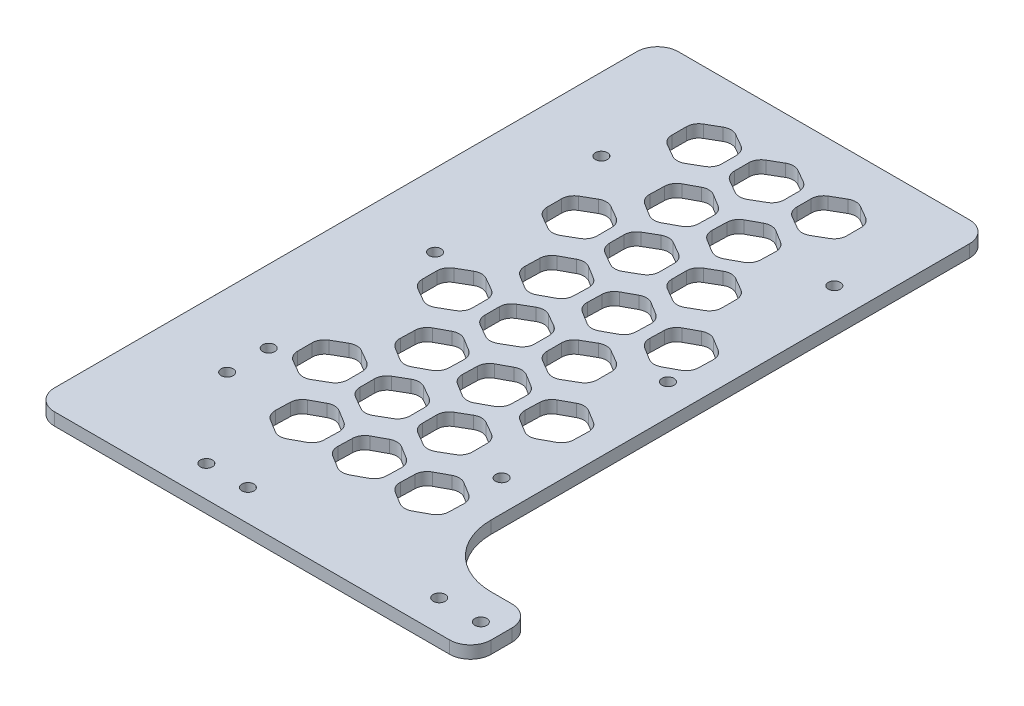
SolidWorks part; units mm, degrees
material "Thornel Mat VMA"
ref_plane "前视基准面" through (0, 0, 0) normal (0, 0, 1) x (1, 0, 0)
ref_plane "上视基准面" through (0, 0, 0) normal (0, 1, 0) x (1, 0, 0)
ref_plane "右视基准面" through (0, 0, 0) normal (1, 0, 0) x (0, 0, -1)
other "Configuration Table"
sketch "草图1" plane through (0, 0, 0) normal (0, 1, 0) x (1, 0, 0)
  line L0 (40, 75) -> (40, -60)
  line L1 (-40, -75) -> (40, -75)
  line L2 (-40, -75) -> (-40, 75)
  line L3 (-40, 75) -> (40, 75)
  line L4 (40, -75) -> (40, 75) construction
  line L5 (-40, -75) -> (40, 75) construction
  line L6 (-40, 75) -> (40, -75) construction
  line L7 (40, -60) -> (65, -60)
  line L8 (65, -60) -> (65, -75)
  line L9 (65, -75) -> (40, -75)
  line L10 (-50.4431, -67.5) -> (109.1266, -67.5) construction
  circle A0 centre (50, -67.5) radius 1.45
  circle A1 centre (60, -67.5) radius 1.45
  point P0 (0, 0)
  dimension "D7" = 10
  dimension "D8" = 2.9
  dimension "D1" = 80
  dimension "D2" = 150
  dimension "D3" = 15
  dimension "D4" = 25
  dimension "D5" = 7.5
  dimension "D6" = 10
extrude "凸台-拉伸1" add sketch "草图1" along normal blind 3
fillet "圆角1" radius 5 5 edges at (40, 1.5, -75) (65, 1.5, 75) (-40, 1.5, 75) (-40, 1.5, -75) (65, 1.5, 60)
fillet "圆角2" radius 15 1 edges at (40, 1.5, 60)
sketch "草图2" plane through (0, 3, 0) normal (0, 1, 0) x (1, 0, 0)
  circle A0 centre (4, -67.5) radius 1.45 construction
  circle A1 centre (-6, -67.5) radius 1.45 construction
  circle A2 centre (-22.5, -46) radius 1.45 construction
  circle A3 centre (-22.5, -36) radius 1.45 construction
  circle A4 centre (4, -67.5) radius 1.45
  circle A5 centre (-6, -67.5) radius 1.45
  circle A6 centre (-22.5, -46) radius 1.45
  circle A7 centre (-22.5, -36) radius 1.45
extrude "切除-拉伸1" cut sketch "草图2" against normal through all
sketch "草图3" plane through (0, 3, 0) normal (0, 1, 0) x (1, 0, 0)
  line L0 (-22.5, -46) -> (-22.5, 81.0235) construction
  line L1 (32.5, 83.4378) -> (32.5, -84.3822) construction
  line L2 (40, -45) -> (40, 70) construction
  line L3 (-35, -75) -> (60, -75) construction
  circle A0 centre (32.5, -35) radius 1.45
  circle A1 centre (32.5, 5) radius 1.45
  circle A2 centre (32.5, 45) radius 1.45
  circle A3 centre (-22.5, 44) radius 1.45
  circle A4 centre (-22.5, 4) radius 1.45
  circle A5 centre (-22.5, -36) radius 1.45 construction
  dimension "D2" = 2.9
  dimension "D3" = 40
  dimension "D4" = 40
  dimension "D5" = 40
  dimension "D6" = 40
  dimension "D7" = 40
  dimension "D1" = 7.5
extrude "切除-拉伸2" cut sketch "草图3" against normal through all
sketch "草图4" plane through (0, 3, 0) normal (0, 1, 0) x (1, 0, 0)
  line L0 (8.5893, 62.0825) -> (2.5893, 65.5466)
  line L1 (-6.4107, 62.0825) -> (-12.4107, 65.5466)
  line L2 (-12.4107, 65.5466) -> (-18.4107, 62.0825)
  line L3 (-18.4107, 62.0825) -> (-18.4107, 55.1543)
  line L4 (-18.4107, 55.1543) -> (-12.4107, 51.6902)
  line L5 (-12.4107, 51.6902) -> (-6.4107, 55.1543)
  line L6 (-6.4107, 55.1543) -> (-6.4107, 62.0825)
  line L7 (3.3955, 46.736) -> (-2.5041, 50.3685)
  line L8 (-2.5041, 50.3685) -> (-8.5997, 47.0755)
  line L9 (-8.5997, 47.0755) -> (-8.7957, 40.15)
  line L10 (-8.7957, 40.15) -> (-2.8961, 36.5176)
  line L11 (-2.8961, 36.5176) -> (3.1995, 39.8106)
  line L12 (3.1995, 39.8106) -> (3.3955, 46.736)
  line L13 (2.5893, 65.5466) -> (-3.4107, 62.0825)
  line L14 (-3.4107, 62.0825) -> (-3.4107, 55.1543)
  line L15 (-3.4107, 55.1543) -> (2.5893, 51.6902)
  line L16 (2.5893, 51.6902) -> (8.5893, 55.1543)
  line L17 (8.5893, 55.1543) -> (8.5893, 62.0825)
  line L18 (18.3955, 46.736) -> (12.4959, 50.3685)
  line L19 (12.4959, 50.3685) -> (6.4003, 47.0755)
  line L20 (6.4003, 47.0755) -> (6.2043, 40.15)
  line L21 (6.2043, 40.15) -> (12.1039, 36.5176)
  line L22 (12.1039, 36.5176) -> (18.1995, 39.8106)
  line L23 (18.1995, 39.8106) -> (18.3955, 46.736)
  line L24 (23.5893, 62.0825) -> (17.5893, 65.5466)
  line L25 (17.5893, 65.5466) -> (11.5893, 62.0825)
  line L26 (11.5893, 62.0825) -> (11.5893, 55.1543)
  line L27 (11.5893, 55.1543) -> (17.5893, 51.6902)
  line L28 (17.5893, 51.6902) -> (23.5893, 55.1543)
  line L29 (23.5893, 55.1543) -> (23.5893, 62.0825)
  line L36 (8.5893, 32.0825) -> (2.5893, 35.5466)
  line L37 (2.5893, 35.5466) -> (-3.4107, 32.0825)
  line L38 (-3.4107, 32.0825) -> (-3.4107, 25.1543)
  line L39 (-3.4107, 25.1543) -> (2.5893, 21.6902)
  line L40 (2.5893, 21.6902) -> (8.5893, 25.1543)
  line L41 (8.5893, 25.1543) -> (8.5893, 32.0825)
  line L42 (18.3955, 16.736) -> (12.4959, 20.3685)
  line L43 (12.4959, 20.3685) -> (6.4003, 17.0755)
  line L44 (6.4003, 17.0755) -> (6.2043, 10.15)
  line L45 (6.2043, 10.15) -> (12.1039, 6.5176)
  line L46 (12.1039, 6.5176) -> (18.1995, 9.8106)
  line L47 (18.1995, 9.8106) -> (18.3955, 16.736)
  line L48 (23.5893, 32.0825) -> (17.5893, 35.5466)
  line L49 (17.5893, 35.5466) -> (11.5893, 32.0825)
  line L50 (11.5893, 32.0825) -> (11.5893, 25.1543)
  line L51 (11.5893, 25.1543) -> (17.5893, 21.6902)
  line L52 (17.5893, 21.6902) -> (23.5893, 25.1543)
  line L53 (23.5893, 25.1543) -> (23.5893, 32.0825)
  line L54 (33.3955, 16.736) -> (27.4959, 20.3685)
  line L55 (27.4959, 20.3685) -> (21.4003, 17.0755)
  line L56 (21.4003, 17.0755) -> (21.2043, 10.15)
  line L57 (21.2043, 10.15) -> (27.1039, 6.5176)
  line L58 (27.1039, 6.5176) -> (33.1995, 9.8106)
  line L59 (33.1995, 9.8106) -> (33.3955, 16.736)
  line L60 (8.5893, 2.0825) -> (2.5893, 5.5466)
  line L61 (2.5893, 5.5466) -> (-3.4107, 2.0825)
  line L62 (-3.4107, 2.0825) -> (-3.4107, -4.8457)
  line L63 (-3.4107, -4.8457) -> (2.5893, -8.3098)
  line L64 (2.5893, -8.3098) -> (8.5893, -4.8457)
  line L65 (8.5893, -4.8457) -> (8.5893, 2.0825)
  line L66 (18.3955, -13.264) -> (12.4959, -9.6315)
  line L67 (12.4959, -9.6315) -> (6.4003, -12.9245)
  line L68 (6.4003, -12.9245) -> (6.2043, -19.85)
  line L69 (6.2043, -19.85) -> (12.1039, -23.4824)
  line L70 (12.1039, -23.4824) -> (18.1995, -20.1894)
  line L71 (18.1995, -20.1894) -> (18.3955, -13.264)
  line L72 (23.5893, 2.0825) -> (17.5893, 5.5466)
  line L73 (17.5893, 5.5466) -> (11.5893, 2.0825)
  line L74 (11.5893, 2.0825) -> (11.5893, -4.8457)
  line L75 (11.5893, -4.8457) -> (17.5893, -8.3098)
  line L76 (17.5893, -8.3098) -> (23.5893, -4.8457)
  line L77 (23.5893, -4.8457) -> (23.5893, 2.0825)
  line L78 (33.3955, -13.264) -> (27.4959, -9.6315)
  line L79 (27.4959, -9.6315) -> (21.4003, -12.9245)
  line L80 (21.4003, -12.9245) -> (21.2043, -19.85)
  line L81 (21.2043, -19.85) -> (27.1039, -23.4824)
  line L82 (27.1039, -23.4824) -> (33.1995, -20.1894)
  line L83 (33.1995, -20.1894) -> (33.3955, -13.264)
  line L84 (8.5893, -27.9175) -> (2.5893, -24.4534)
  line L85 (2.5893, -24.4534) -> (-3.4107, -27.9175)
  line L86 (-3.4107, -27.9175) -> (-3.4107, -34.8457)
  line L87 (-3.4107, -34.8457) -> (2.5893, -38.3098)
  line L88 (2.5893, -38.3098) -> (8.5893, -34.8457)
  line L89 (8.5893, -34.8457) -> (8.5893, -27.9175)
  line L90 (18.3955, -43.264) -> (12.4959, -39.6315)
  line L91 (12.4959, -39.6315) -> (6.4003, -42.9245)
  line L92 (6.4003, -42.9245) -> (6.2043, -49.85)
  line L93 (6.2043, -49.85) -> (12.1039, -53.4824)
  line L94 (12.1039, -53.4824) -> (18.1995, -50.1894)
  line L95 (18.1995, -50.1894) -> (18.3955, -43.264)
  line L96 (23.5893, -27.9175) -> (17.5893, -24.4534)
  line L97 (17.5893, -24.4534) -> (11.5893, -27.9175)
  line L98 (11.5893, -27.9175) -> (11.5893, -34.8457)
  line L99 (11.5893, -34.8457) -> (17.5893, -38.3098)
  line L100 (17.5893, -38.3098) -> (23.5893, -34.8457)
  line L101 (23.5893, -34.8457) -> (23.5893, -27.9175)
  line L102 (33.3955, -43.264) -> (27.4959, -39.6315)
  line L103 (27.4959, -39.6315) -> (21.4003, -42.9245)
  line L104 (21.4003, -42.9245) -> (21.2043, -49.85)
  line L105 (21.2043, -49.85) -> (27.1039, -53.4824)
  line L106 (27.1039, -53.4824) -> (33.1995, -50.1894)
  line L107 (33.1995, -50.1894) -> (33.3955, -43.264)
  line L108 (-6.4107, 32.0825) -> (-12.4107, 35.5466)
  line L109 (-12.4107, 35.5466) -> (-18.4107, 32.0825)
  line L110 (-18.4107, 32.0825) -> (-18.4107, 25.1543)
  line L111 (-18.4107, 25.1543) -> (-12.4107, 21.6902)
  line L112 (-12.4107, 21.6902) -> (-6.4107, 25.1543)
  line L113 (-6.4107, 25.1543) -> (-6.4107, 32.0825)
  line L114 (3.3955, 16.736) -> (-2.5041, 20.3685)
  line L115 (-2.5041, 20.3685) -> (-8.5997, 17.0755)
  line L116 (-8.5997, 17.0755) -> (-8.7957, 10.15)
  line L117 (-8.7957, 10.15) -> (-2.8961, 6.5176)
  line L118 (-2.8961, 6.5176) -> (3.1995, 9.8106)
  line L119 (3.1995, 9.8106) -> (3.3955, 16.736)
  line L120 (-6.4107, 2.0825) -> (-12.4107, 5.5466)
  line L121 (-12.4107, 5.5466) -> (-18.4107, 2.0825)
  line L122 (-18.4107, 2.0825) -> (-18.4107, -4.8457)
  line L123 (-18.4107, -4.8457) -> (-12.4107, -8.3098)
  line L124 (-12.4107, -8.3098) -> (-6.4107, -4.8457)
  line L125 (-6.4107, -4.8457) -> (-6.4107, 2.0825)
  line L126 (3.3955, -13.264) -> (-2.5041, -9.6315)
  line L127 (-2.5041, -9.6315) -> (-8.5997, -12.9245)
  line L128 (-8.5997, -12.9245) -> (-8.7957, -19.85)
  line L129 (-8.7957, -19.85) -> (-2.8961, -23.4824)
  line L130 (-2.8961, -23.4824) -> (3.1995, -20.1894)
  line L131 (3.1995, -20.1894) -> (3.3955, -13.264)
  line L132 (-6.4107, -27.9175) -> (-12.4107, -24.4534)
  line L133 (-12.4107, -24.4534) -> (-18.4107, -27.9175)
  line L134 (-18.4107, -27.9175) -> (-18.4107, -34.8457)
  line L135 (-18.4107, -34.8457) -> (-12.4107, -38.3098)
  line L136 (-12.4107, -38.3098) -> (-6.4107, -34.8457)
  line L137 (-6.4107, -34.8457) -> (-6.4107, -27.9175)
  line L138 (3.3955, -43.264) -> (-2.5041, -39.6315)
  line L139 (-2.5041, -39.6315) -> (-8.5997, -42.9245)
  line L140 (-8.5997, -42.9245) -> (-8.7957, -49.85)
  line L141 (-8.7957, -49.85) -> (-2.8961, -53.4824)
  line L142 (-2.8961, -53.4824) -> (3.1995, -50.1894)
  line L143 (3.1995, -50.1894) -> (3.3955, -43.264)
  line L144 (27.4959, 50.3685) -> (21.4003, 47.0755) [skipped]
  line L145 (21.4003, 47.0755) -> (21.2043, 40.15) [skipped]
  line L146 (21.2043, 40.15) -> (27.1039, 36.5176) [skipped]
  line L147 (33.1995, 39.8106) -> (33.3955, 46.736) [skipped]
  line L148 (33.3955, 46.736) -> (27.4959, 50.3685) [skipped]
  line L149 (27.1039, 36.5176) -> (33.1995, 39.8106) [skipped]
  circle A0 centre (-12.4107, 58.6184) radius 6 construction
  circle A1 centre (-2.7001, 43.443) radius 6 construction
  point P1 (-5.5519, 48.722)
  dimension "D1" = 12
  dimension "D2" = 12
  dimension "D3" = 6
  dimension "D4" = 3
  dimension "D5" = 4
extrude "切除-拉伸3" cut sketch "草图4" against normal through all
fillet "圆角3" radius 3 131 edges at (-6.4107, 1.5, -55.1543) (-12.4107, 1.5, -51.6902) (-18.4107, 1.5, -55.1543) (-6.4107, 1.5, -62.0825) (3.1995, 1.5, 50.1894) (-2.8961, 1.5, 53.4824) (-8.7957, 1.5, 49.85) (-8.5997, 1.5, 42.9245) (-2.5041, 1.5, 39.6315) (3.3955, 1.5, 43.264) (-6.4107, 1.5, 34.8457) (-12.4107, 1.5, 38.3098) (-18.4107, 1.5, 34.8457) (-18.4107, 1.5, 27.9175) (-12.4107, 1.5, 24.4534) (-6.4107, 1.5, 27.9175) (3.1995, 1.5, 20.1894) (-2.8961, 1.5, 23.4824) (-8.7957, 1.5, 19.85) (-8.5997, 1.5, 12.9245) (-2.5041, 1.5, 9.6315) (3.3955, 1.5, 13.264) (-6.4107, 1.5, 4.8457) (-12.4107, 1.5, 8.3098) (-18.4107, 1.5, 4.8457) (-18.4107, 1.5, -2.0825) (-12.4107, 1.5, -5.5466) (-6.4107, 1.5, -2.0825) (3.1995, 1.5, -9.8106) (-2.8961, 1.5, -6.5176) (-8.7957, 1.5, -10.15) (-8.5997, 1.5, -17.0755) (-2.5041, 1.5, -20.3685) (3.3955, 1.5, -16.736) (-6.4107, 1.5, -25.1543) (-12.4107, 1.5, -21.6902) (-18.4107, 1.5, -25.1543) (-18.4107, 1.5, -32.0825) (-12.4107, 1.5, -35.5466) (8.5893, 1.5, 34.8457) (2.5893, 1.5, 38.3098) (-3.4107, 1.5, 34.8457) (2.5893, 1.5, 24.4534) (8.5893, 1.5, 27.9175) (18.1995, 1.5, 50.1894) (12.1039, 1.5, 53.4824) (6.2043, 1.5, 49.85) (6.4003, 1.5, 42.9245) (18.3955, 1.5, 43.264) (23.5893, 1.5, 34.8457) (17.5893, 1.5, 38.3098) (11.5893, 1.5, 34.8457) (11.5893, 1.5, 27.9175) (17.5893, 1.5, 24.4534) (23.5893, 1.5, 27.9175) (33.1995, 1.5, 50.1894) (27.1039, 1.5, 53.4824) (21.2043, 1.5, 49.85) (21.4003, 1.5, 42.9245) (27.4959, 1.5, 39.6315) (8.5893, 1.5, 4.8457) (2.5893, 1.5, 8.3098) (-3.4107, 1.5, 4.8457) (-3.4107, 1.5, -2.0825) (2.5893, 1.5, -5.5466) (8.5893, 1.5, -2.0825) (18.1995, 1.5, 20.1894) (12.1039, 1.5, 23.4824) (6.2043, 1.5, 19.85) (12.4959, 1.5, 9.6315) (18.3955, 1.5, 13.264) (23.5893, 1.5, 4.8457) (17.5893, 1.5, 8.3098) (11.5893, 1.5, 4.8457) (11.5893, 1.5, -2.0825) (23.5893, 1.5, -2.0825) (33.1995, 1.5, 20.1894) (27.1039, 1.5, 23.4824) (21.2043, 1.5, 19.85) (21.4003, 1.5, 12.9245) (27.4959, 1.5, 9.6315) (33.3955, 1.5, 13.264) (8.5893, 1.5, -25.1543) (2.5893, 1.5, -21.6902) (-3.4107, 1.5, -32.0825) (2.5893, 1.5, -35.5466) (8.5893, 1.5, -32.0825) (18.1995, 1.5, -9.8106) (12.1039, 1.5, -6.5176) (6.2043, 1.5, -10.15) (6.4003, 1.5, -17.0755) (12.4959, 1.5, -20.3685) (18.3955, 1.5, -16.736) (23.5893, 1.5, -25.1543) (17.5893, 1.5, -21.6902) (11.5893, 1.5, -25.1543) (11.5893, 1.5, -32.0825) (17.5893, 1.5, -35.5466) (23.5893, 1.5, -32.0825) (33.1995, 1.5, -9.8106) (27.1039, 1.5, -6.5176) (21.2043, 1.5, -10.15) (21.4003, 1.5, -17.0755) (27.4959, 1.5, -20.3685) (33.3955, 1.5, -16.736) (3.1995, 1.5, -39.8106) (-2.8961, 1.5, -36.5176) (-8.7957, 1.5, -40.15) (-8.5997, 1.5, -47.0755) (-2.5041, 1.5, -50.3685) (3.3955, 1.5, -46.736) (8.5893, 1.5, -55.1543) (2.5893, 1.5, -51.6902) (-3.4107, 1.5, -55.1543) (-3.4107, 1.5, -62.0825) (2.5893, 1.5, -65.5466) (8.5893, 1.5, -62.0825) (18.1995, 1.5, -39.8106) (12.1039, 1.5, -36.5176) (6.2043, 1.5, -40.15) (6.4003, 1.5, -47.0755) (12.4959, 1.5, -50.3685) (18.3955, 1.5, -46.736) (23.5893, 1.5, -55.1543) (17.5893, 1.5, -51.6902) (11.5893, 1.5, -55.1543) (11.5893, 1.5, -62.0825) (17.5893, 1.5, -65.5466) (23.5893, 1.5, -62.0825) (-12.4107, 1.5, -65.5466) (-18.4107, 1.5, -62.0825)
